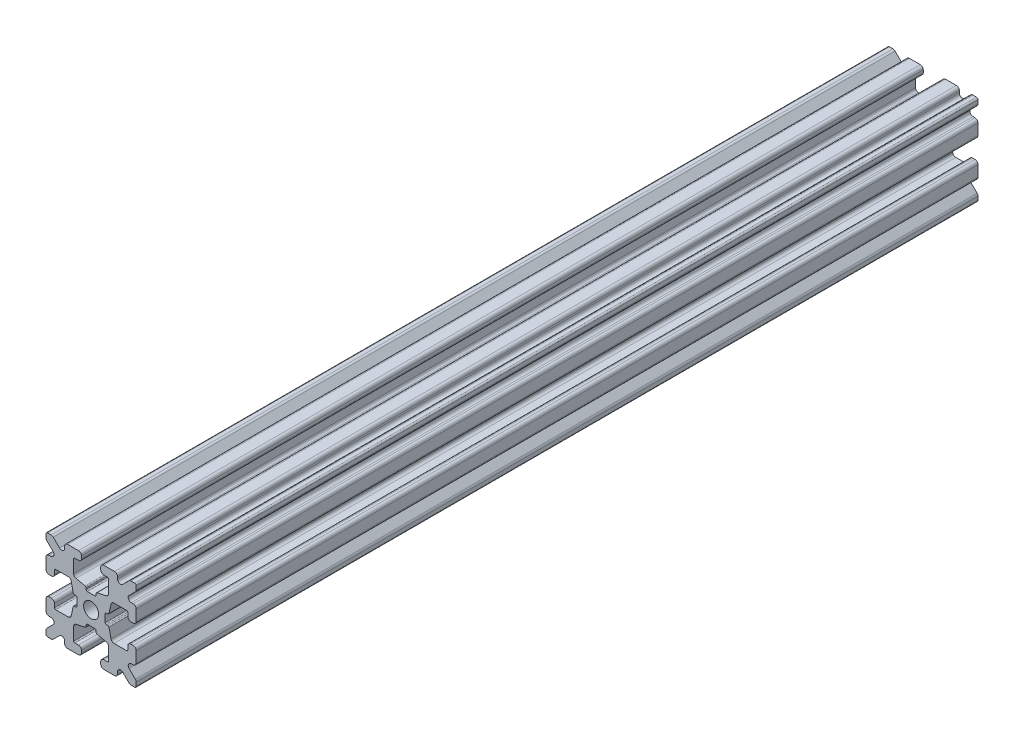
SolidWorks part; units mm, degrees
ref_plane "Front Plane" through (0, 0, 0) normal (0, 0, 1) x (1, 0, 0)
ref_plane "Top Plane" through (0, 0, 0) normal (0, 1, 0) x (1, 0, 0)
ref_plane "Right Plane" through (0, 0, 0) normal (1, 0, 0) x (0, 0, -1)
sketch "Sketch1" plane through (0, 0, 0) normal (0, 0, 1) x (1, 0, 0)
  line L1 (-7.5, -7.5) -> (7.5, -7.5)
  line L2 (-7.5, -7.5) -> (-7.5, 7.5)
  line L3 (-7.5, 7.5) -> (7.5, 7.5)
  line L4 (7.5, -7.5) -> (7.5, 7.5)
  line L5 (-7.5, -7.5) -> (7.5, 7.5) construction
  line L6 (-7.5, 7.5) -> (7.5, -7.5) construction
  circle A0 centre (0, 0) radius 1.25
  point P0 (0, 0)
  dimension "D2" = 2.5
  dimension "D1" = 15
extrude "Boss-Extrude1" add sketch "Sketch1" along normal mid plane 140
fillet "Fillet1" radius 0.25 4 edges at (7.5, -7.5, 0) (-7.5, -7.5, 0) (7.5, 7.5, 0) (-7.5, 7.5, 0)
sketch "Sketch2" plane through (0, 0, 70) normal (0, 0, 1) x (1, 0, 0)
  line L0 (-7.5, 7.25) -> (-7.5, -7.25) construction
  line L1 (-7.5, 1.6) -> (-6.1, 1.6)
  line L2 (-7.5, 1.6) -> (-7.5, -1.6)
  line L3 (-7.5, -1.6) -> (-6.1, -1.6)
  line L4 (-6.1, 1.6) -> (-6.1, 2.9)
  line L5 (0, 0) -> (-12.1036, 0) construction
  line L6 (-6.1, -2.9) -> (-3.4, -2.9)
  line L7 (0, 0) -> (-7.25, 7.25) construction
  line L8 (-6.1, 2.9) -> (-3.4, 2.9)
  line L9 (-3.4, -2.9) -> (-3.4, 2.9)
  line L10 (55, 0) -> (-55, 0) construction
  line L11 (-6.1, -2.9) -> (-6.1, -1.6)
  line L12 (2.9, 6.1) -> (1.6, 6.1)
  line L13 (2.9, 3.4) -> (-2.9, 3.4)
  line L14 (-2.9, 6.1) -> (-2.9, 3.4)
  line L15 (2.9, 6.1) -> (2.9, 3.4)
  line L16 (-1.6, 6.1) -> (-2.9, 6.1)
  line L17 (1.6, 7.5) -> (1.6, 6.1)
  line L18 (-1.6, 7.5) -> (1.6, 7.5)
  line L19 (-1.6, 7.5) -> (-1.6, 6.1)
  line L20 (-1.6, -7.5) -> (-1.6, -6.1)
  line L21 (-1.6, -7.5) -> (1.6, -7.5)
  line L22 (1.6, -7.5) -> (1.6, -6.1)
  line L23 (-1.6, -6.1) -> (-2.9, -6.1)
  line L24 (2.9, -6.1) -> (2.9, -3.4)
  line L25 (-2.9, -6.1) -> (-2.9, -3.4)
  line L26 (2.9, -3.4) -> (-2.9, -3.4)
  line L27 (2.9, -6.1) -> (1.6, -6.1)
  line L28 (6.1, -2.9) -> (6.1, -1.6)
  line L29 (3.4, -2.9) -> (3.4, 2.9)
  line L30 (6.1, 2.9) -> (3.4, 2.9)
  line L31 (6.1, -2.9) -> (3.4, -2.9)
  line L32 (6.1, 1.6) -> (6.1, 2.9)
  line L33 (7.5, -1.6) -> (6.1, -1.6)
  line L34 (7.5, 1.6) -> (7.5, -1.6)
  line L35 (7.5, 1.6) -> (6.1, 1.6)
  dimension "D1" = 3.2
  dimension "D2" = 5.8
  dimension "D3" = 1.4
  dimension "D4" = 2.7
extrude "Cut-Extrude1" cut sketch "Sketch2" against normal through all
sketch "Sketch4" plane through (0, 0, 70) normal (0, 0, 1) x (1, 0, 0)
  line L0 (-3.4, 2.9) -> (-2.75, 0)
  line L1 (55, 0) -> (-55, 0) construction
  line L2 (-2.75, 0) -> (-3.4, -2.9)
  line L3 (-3.4, -2.9) -> (-3.4, 2.9) construction
  line L4 (-3.4, 2.9) -> (-3.4, -2.9)
  line L5 (-2.9, 3.4) -> (0, 2.75)
  line L6 (0, 2.75) -> (2.9, 3.4)
  line L7 (2.9, 3.4) -> (-2.9, 3.4)
  line L8 (3.4, 2.9) -> (2.75, 0)
  line L9 (2.75, 0) -> (3.4, -2.9)
  line L10 (3.4, -2.9) -> (3.4, 2.9)
  line L11 (-2.9, -3.4) -> (0, -2.75)
  line L12 (0, -2.75) -> (2.9, -3.4)
  line L13 (2.9, -3.4) -> (-2.9, -3.4)
  circle A2 centre (0, 0) radius 2.75
  circle A3 centre (0, 0) radius 2.75 construction
  dimension "D1" = 1.5
extrude "Cut-Extrude3" cut sketch "Sketch4" against normal through all
fillet "Fillet3" radius 0.5 16 edges at (-6.1, -1.6, 0) (-7.5, -1.6, 0) (-6.1, 1.6, 0) (-7.5, 1.6, 0) (-1.6, -7.5, 0) (-1.6, -6.1, 0) (1.6, -7.5, 0) (1.6, -6.1, 0) (6.1, -1.6, 0) (7.5, -1.6, 0) (7.5, 1.6, 0) (6.1, 1.6, 0) (1.6, 7.5, 0) (1.6, 6.1, 0) (-1.6, 7.5, 0) (-1.6, 6.1, 0)
fillet "Fillet4" radius 0.5 8 edges at (-3.4, 2.9, 0) (-3.4, -2.9, 0) (2.9, -3.4, 0) (-2.9, -3.4, 0) (3.4, -2.9, 0) (3.4, 2.9, 0) (-2.9, 3.4, 0) (2.9, 3.4, 0)
fillet "Fillet5" radius 3 4 edges at (0, -2.75, 0) (2.75, 0, 0) (-2.75, 0, 0) (0, 2.75, 0)
fillet "Fillet6" radius 0.2 8 edges at (-2.9, -6.1, 0) (2.9, -6.1, 0) (6.1, -2.9, 0) (6.1, 2.9, 0) (2.9, 6.1, 0) (-2.9, 6.1, 0) (-6.1, -2.9, 0) (-6.1, 2.9, 0)
sketch "Sketch5" plane through (0, 0, 70) normal (0, 0, 1) x (1, 0, 0)
  line L0 (0, 0) -> (-7.25, 7.25) construction
  line L1 (-7.5, 6.4393) -> (-5.4607, 4.4)
  line L2 (-6.4393, 7.5) -> (-4.4, 5.4607)
  line L3 (-7.5, 4.4) -> (-5.4607, 4.4)
  line L4 (-3.8003, 2.9) -> (-5.9, 2.9) construction
  line L5 (0, 0) -> (-12.1819, 0) construction
  line L6 (-4.4, 7.5) -> (-4.4, 5.4607)
  line L7 (-2.9, 5.9) -> (-2.9, 3.8003) construction
  line L8 (-7.5, 6.4393) -> (-7.5, 4.4)
  line L9 (-7.5, 7.25) -> (-7.5, 2.1) construction
  line L10 (2.1, -7.5) -> (7.25, -7.5) construction
  line L11 (7.5, -7.25) -> (7.5, -2.1) construction
  line L12 (7.25, 7.5) -> (2.1, 7.5) construction
  line L13 (-2.1, 7.5) -> (-7.25, 7.5) construction
  line L14 (-4.4, 7.5) -> (-6.4393, 7.5)
  line L16 (55, 0) -> (-55, 0) construction
  line L17 (0, 0) -> (0, 10.993) construction
  line L18 (0, -54.6431) -> (0, 54.6431) construction
  line L20 (4.4, 7.5) -> (6.4393, 7.5)
  line L22 (7.5, 6.4393) -> (7.5, 4.4)
  line L23 (4.4, 7.5) -> (4.4, 5.4607)
  line L24 (7.5, 4.4) -> (5.4607, 4.4)
  line L25 (6.4393, 7.5) -> (4.4, 5.4607)
  line L26 (7.5, 6.4393) -> (5.4607, 4.4)
  line L27 (7.5, -6.4393) -> (5.4607, -4.4)
  line L28 (6.4393, -7.5) -> (4.4, -5.4607)
  line L29 (7.5, -4.4) -> (5.4607, -4.4)
  line L30 (4.4, -7.5) -> (4.4, -5.4607)
  line L31 (7.5, -6.4393) -> (7.5, -4.4)
  line L33 (4.4, -7.5) -> (6.4393, -7.5)
  line L36 (-4.4, -7.5) -> (-6.4393, -7.5)
  line L38 (-7.5, -6.4393) -> (-7.5, -4.4)
  line L39 (-4.4, -7.5) -> (-4.4, -5.4607)
  line L40 (-7.5, -4.4) -> (-5.4607, -4.4)
  line L41 (-6.4393, -7.5) -> (-4.4, -5.4607)
  line L42 (-7.5, -6.4393) -> (-5.4607, -4.4)
  dimension "D1" = 1.5
  dimension "D2" = 1.5
  dimension "D3" = 1.5
extrude "Cut-Extrude4" cut sketch "Sketch5" against normal through all
fillet "Fillet8" radius 0.5 24 edges at (-5.4607, 4.4, 0) (-7.5, 4.4, 0) (-5.4607, -4.4, 0) (-7.5, -4.4, 0) (-4.4, -7.5, 0) (-4.4, -5.4607, 0) (4.4, -7.5, 0) (4.4, -5.4607, 0) (5.4607, -4.4, 0) (7.5, -4.4, 0) (7.5, 4.4, 0) (5.4607, 4.4, 0) (4.4, 5.4607, 0) (4.4, 7.5, 0) (-4.4, 5.4607, 0) (-4.4, 7.5, 0) (-6.4393, 7.5, 0) (-7.5, 6.4393, 0) (6.4393, 7.5, 0) (7.5, 6.4393, 0) (6.4393, -7.5, 0) (7.5, -6.4393, 0) (-6.4393, -7.5, 0) (-7.5, -6.4393, 0)
sketch "Sketch6" plane through (0, 0, 70) normal (0, 0, 1) x (1, 0, 0)
  line L0 (0, 0) -> (0, 11.013) construction
  line L1 (0.6561, 2.8971) -> (2.1235, 2.8971) construction
  line L2 (0, -54.6431) -> (0, 54.6431) construction
  line L3 (0, 0) -> (7.25, 7.25) construction
  line L4 (7.5, 0.8255) -> (7.5, -0.8255)
  line L5 (2.3471, 0.8255) -> (7.5, 0.8255)
  line L6 (0, 0) -> (12.4016, 0) construction
  line L7 (0.8255, -7.5) -> (-0.8255, -7.5)
  line L8 (2.3471, -0.8255) -> (2.3471, 0.8255)
  line L9 (0.8255, -2.3471) -> (0.8255, -7.5)
  line L10 (7.5, -0.8255) -> (2.3471, -0.8255)
  line L11 (-7.5, -0.8255) -> (-2.3471, -0.8255)
  line L12 (-2.3471, -0.8255) -> (-2.3471, 0.8255)
  line L13 (-0.8255, -2.3471) -> (0.8255, -2.3471)
  line L14 (-0.8255, 7.5) -> (-0.8255, 2.3471)
  line L15 (-0.8255, 2.3471) -> (0.8255, 2.3471)
  line L16 (-0.8255, -7.5) -> (-0.8255, -2.3471)
  line L17 (0.8255, 2.3471) -> (0.8255, 7.5)
  line L18 (0.8255, 7.5) -> (-0.8255, 7.5)
  line L19 (3.9, 7.5) -> (2.1, 7.5) construction
  line L20 (-2.3471, 0.8255) -> (-7.5, 0.8255)
  line L21 (-7.5, 0.8255) -> (-7.5, -0.8255)
  point P5 (0, -2.5973)
  point P7 (0, 2.5973)
  dimension "D3" = 0.55
  dimension "D1" = 1.651
extrude "Cut-Extrude5" cut sketch "Sketch6" against normal through all
fillet "Fillet10" radius 0.2 16 edges at (-2.935, 0.8255, 0) (-2.935, -0.8255, 0) (2.935, -0.8255, 0) (2.935, 0.8255, 0) (0.8255, 2.935, 0) (-0.8255, 2.935, 0) (-2.3471, 0.8255, 0) (-2.3471, -0.8255, 0) (0.8255, 2.3471, 0) (-0.8255, 2.3471, 0) (2.3471, 0.8255, 0) (2.3471, -0.8255, 0) (0.8255, -2.935, 0) (0.8255, -2.3471, 0) (-0.8255, -2.3471, 0) (-0.8255, -2.935, 0)
